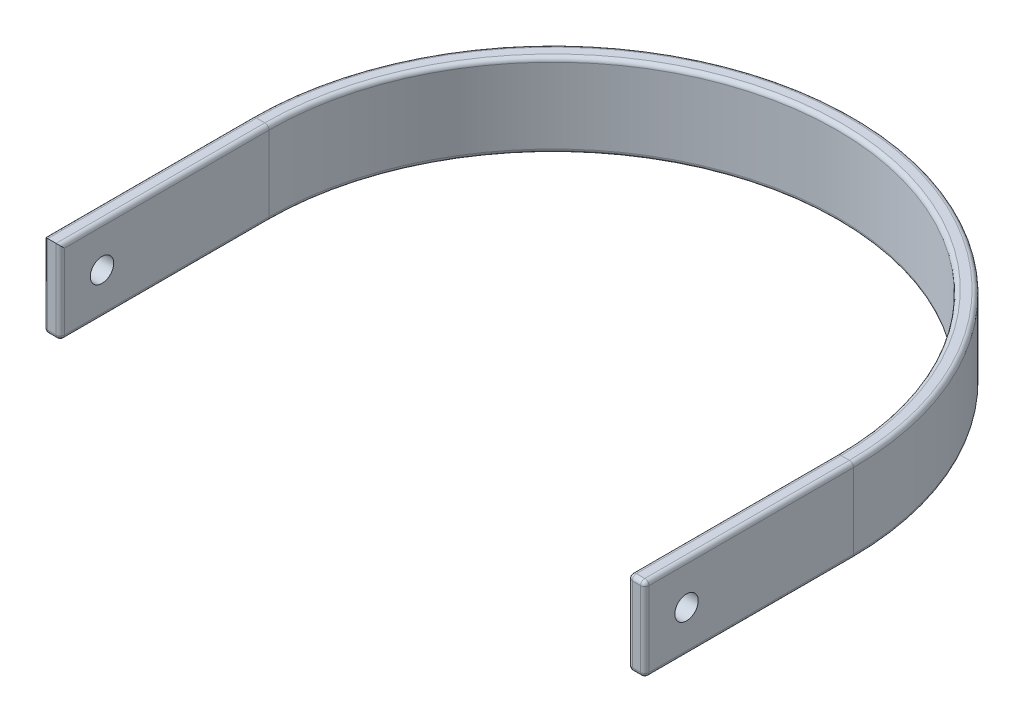
SolidWorks part; units mm, degrees
ref_plane "Płaszczyzna przednia" through (0, 0, 0) normal (0, 0, 1) x (1, 0, 0)
ref_plane "Płaszczyzna górna" through (0, 0, 0) normal (0, 1, 0) x (1, 0, 0)
ref_plane "Płaszczyzna prawa" through (0, 0, 0) normal (1, 0, 0) x (0, 0, -1)
sketch "Szkic2" plane through (0, 0, 0) normal (0, 1, 0) x (1, 0, 0)
  line L0 (0, 0) -> (0, 25)
  line L2 (70, 25) -> (70, 0)
  arc A0 (0, 25) -> (70, 25) centre (35, 25) cw
  dimension "D3" = 35
  dimension "D1" = 25
  dimension "D2" = 70
sketch "Szkic3" plane through (0, 0, 0) normal (0, 0, 1) x (1, 0, 0)
  line L1 (-1, 5) -> (1, 5)
  line L2 (-1, 5) -> (-1, -5)
  line L3 (-1, -5) -> (1, -5)
  line L4 (1, 5) -> (1, -5)
  line L5 (-1, 5) -> (1, -5) construction
  line L6 (-1, -5) -> (1, 5) construction
  point P0 (0, 0)
  dimension "D1" = 2
  dimension "D2" = 10
sweep "Wyciągnięcie po ścieżce1" add profiles "Szkic3" path "Szkic2"
sketch "Szkic5" plane through (-1, 0, 0) normal (-1, 0, 0) x (0, 0, 1)
  line L0 (0, 5) -> (-25, 5) construction
  line L1 (0, 5) -> (0, -5) construction
  circle A0 centre (-5, 0) radius 1.4
  dimension "D1" = 2.8
  dimension "D2" = 5
  dimension "D3" = 5
extrude "Wytnij-wyciągnięcie1" cut sketch "Szkic5" against normal blind 100 contours A0
fillet "Zaokrąglenie1" radius 0.5 19 edges at (35, -5, -61) (35, 5, -61) (1, 0, 0) (-1, 0, 0) (0, -5, 0) (1, -5, -12.5) (35, -5, -59) (70, -5, 0) (71, -5, -12.5) (71, 0, 0) (71, 5, -12.5) (70, 5, 0) (69, 0, 0) (69, -5, -12.5) (69, 5, -12.5) (-1, -5, -12.5) (35, 5, -59) (1, 5, -12.5) (-1, 5, -12.5)
